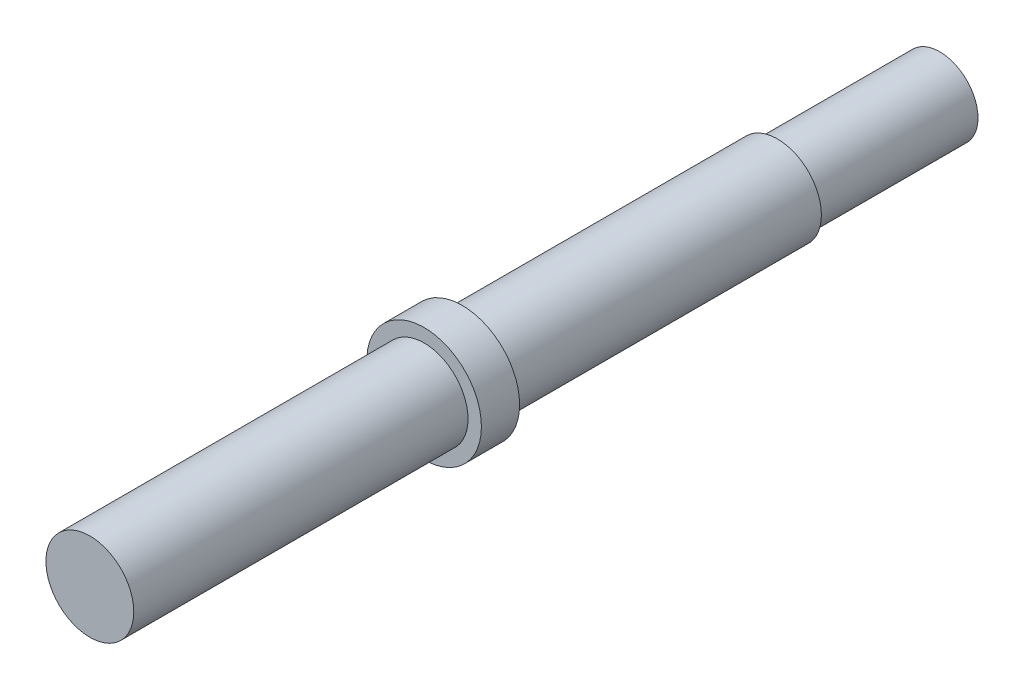
SolidWorks part; units mm, degrees
ref_plane "Front Plane" through (0, 0, 0) normal (0, 0, 1) x (1, 0, 0)
ref_plane "Top Plane" through (0, 0, 0) normal (0, 1, 0) x (1, 0, 0)
ref_plane "Right Plane" through (0, 0, 0) normal (1, 0, 0) x (0, 0, -1)
sketch "Sketch1" plane through (0, 0, 0) normal (0, 0, 1) x (1, 0, 0)
  circle A0 centre (0, 0) radius 4
  dimension "D1" = 8
extrude "Boss-Extrude1" add sketch "Sketch1" against normal blind 17 from offset 12
sketch "Sketch2" plane through (0, 0, 0) normal (0, 0, 1) x (1, 0, 0)
  circle A0 centre (0, 0) radius 4.6
  dimension "D1" = 9.2
extrude "Boss-Extrude2" add sketch "Sketch2" along normal blind 72 from offset 12
sketch "Sketch3" plane through (0, 0, 0) normal (0, 0, 1) x (1, 0, 0)
  circle A0 centre (0, 0) radius 6
  dimension "D1" = 12
extrude "Boss-Extrude3" add sketch "Sketch3" against normal blind 4 from offset 49
sketch "Sketch4" plane through (0, 0, 0) normal (1, 0, 0) x (0, 0, -1)
  line L0 (-84, 0) -> (5, 0) construction
  line L1 (-84, 4.6) -> (-84, -4.6) construction
  line L2 (5, -4) -> (5, 4) construction
